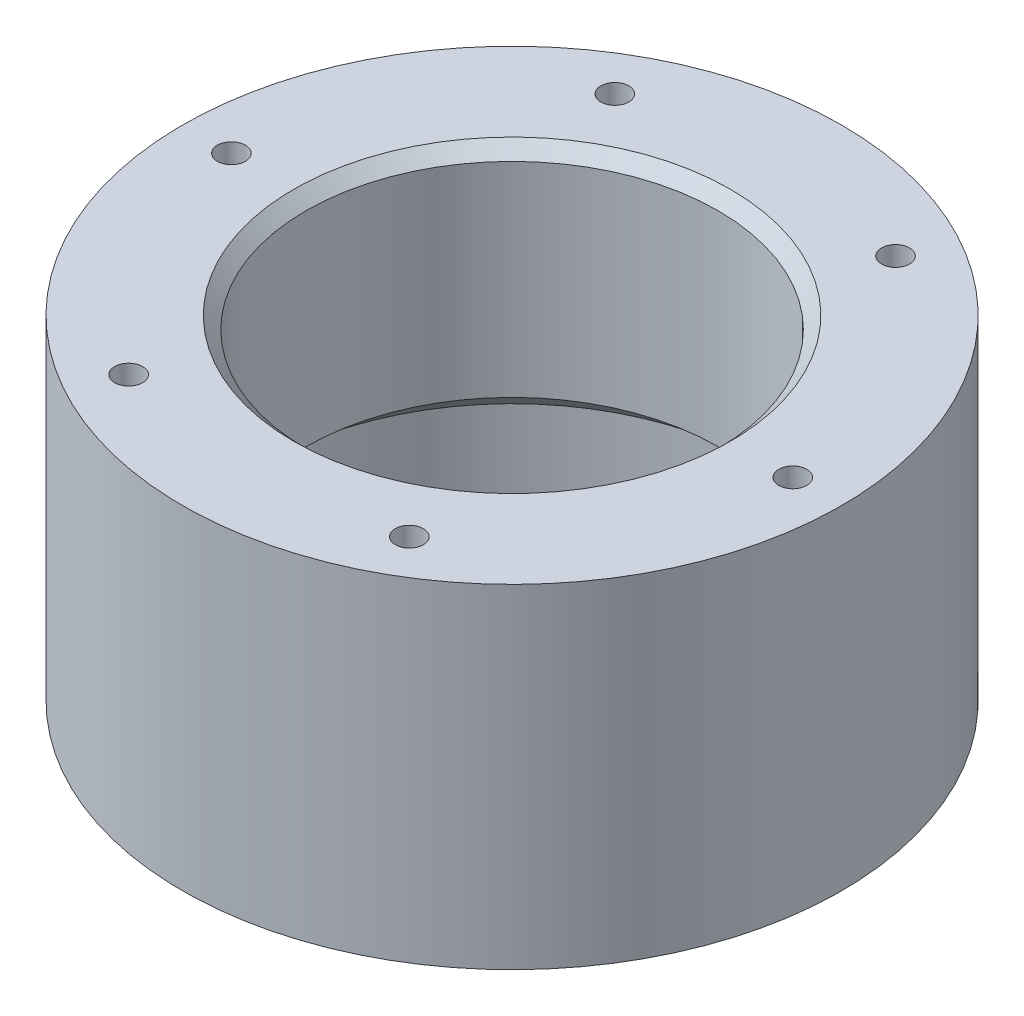
SolidWorks part; units mm, degrees
ref_plane "Płaszczyzna przednia" through (0, 0, 0) normal (0, 0, 1) x (1, 0, 0)
ref_plane "Płaszczyzna górna" through (0, 0, 0) normal (0, 1, 0) x (1, 0, 0)
ref_plane "Płaszczyzna prawa" through (0, 0, 0) normal (1, 0, 0) x (0, 0, -1)
sketch "Szkic1" plane through (0, 0, 0) normal (0, 0, 1) x (1, 0, 0)
  line L0 (0, 0) -> (0, 74.4939) construction
  line L1 (-50, 73.4723) -> (-50, 23.8633)
  line L2 (-53, 76.4723) -> (-80, 76.4723)
  line L3 (-80, 76.4723) -> (-80, -4.5277)
  line L4 (-80, -4.5277) -> (-60, -4.5277)
  line L5 (-60, 76.4723) -> (-60, -4.5277)
  line L6 (-60, -4.5277) -> (-60, 15.4723)
  line L7 (-60, 15.4723) -> (-50, 23.8633)
  line L8 (-60, 15.4723) -> (-42.1791, 15.4723) construction
  line L9 (-50, 73.4723) -> (-53, 76.4723)
  point P3 (-50, 76.4723)
  dimension "D1" = 50
  dimension "D2" = 80
  dimension "D3" = 60
  dimension "D4" = 40
revolve "Obrót1" add sketch "Szkic1" angle 360 about L0
cosmetic thread "Oznaczenie gwintu1" parameters "D1"=20, "D2"=125
ref_plane "Płaszczyzna1" through (0, 76.4723, 0) normal (0, 1, 0) x (1, 0, 0)
sketch "Szkic4" plane through (0, 76.4723, 0) normal (0, 1, 0) x (1, 0, 0)
  line L1 (68.1367, 0) -> (34.0684, 59.0081)
  line L2 (34.0684, 59.0081) -> (-34.0684, 59.0081)
  line L3 (-34.0684, 59.0081) -> (-68.1367, 0)
  line L4 (-68.1367, 0) -> (-34.0684, -59.0081)
  line L5 (-34.0684, -59.0081) -> (34.0684, -59.0081)
  line L6 (34.0684, -59.0081) -> (68.1367, 0)
  circle A0 centre (0, 0) radius 59.0081 construction
  dimension "D1" = 68.1367
hole_wizard "Otwór gwintowany M81" positions "Szkic 3D2" profile "Szkic5" tap size "M8" standard "GB"
sketch3d "Szkic 3D2"
  point P0 (-68.1367, 76.4723, 0)
  point P3 (-34.0684, 76.4723, -59.0081)
  point P6 (34.0684, 76.4723, -59.0081)
  point P9 (68.1367, 76.4723, 0)
  point P12 (34.0684, 76.4723, 59.0081)
  point P15 (-34.0684, 76.4723, 59.0081)
sketch "Szkic5" plane through (-68.1367, 76.4723, 0) normal (1, 0, 0) x (0, 0, 1)
  line L0 (0, 0) -> (0, 42.0429)
  line L1 (0, 42.0429) -> (3.4, 40)
  line L2 (3.4, 40) -> (3.4, 0)
  line L5 (3.4, 0) -> (0, 0)
  line L10 (0, 42.0429) -> (-3.4, 40) construction
  line L11 (0, -6.35) -> (0, 107.95) construction
  dimension "Średnica wiertła gwintu" = 6.8
  dimension "Głębokość otworu gwintowanego" = 40
  dimension "Kąt wiertła" = 118
cosmetic thread "Gwint otworu1" parameters "D1"=35, "D2"=8
cosmetic thread "Gwint otworu2" parameters "D1"=35, "D2"=8
cosmetic thread "Gwint otworu3" parameters "D1"=35, "D2"=8
cosmetic thread "Gwint otworu4" parameters "D1"=35, "D2"=8
cosmetic thread "Gwint otworu5" parameters "D1"=35, "D2"=8
cosmetic thread "Gwint otworu6" parameters "D1"=35, "D2"=8
